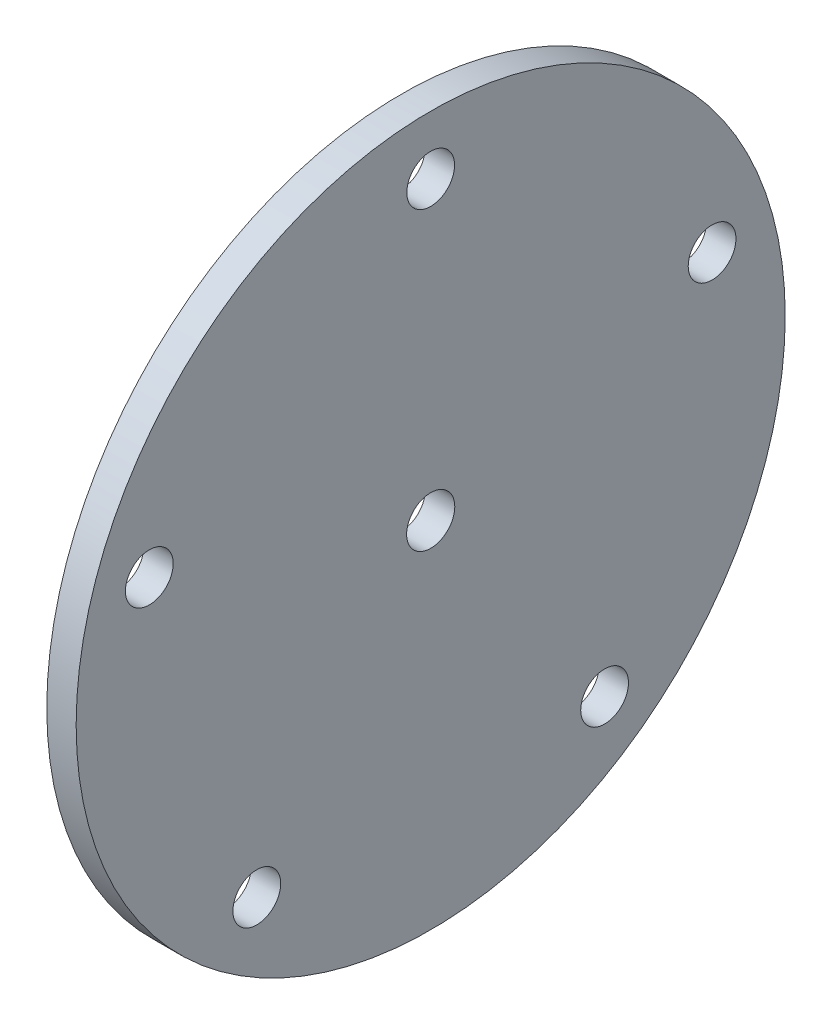
SolidWorks part; units mm, degrees
material "6061 Alloy"
ref_plane "Front Plane" through (0, 0, 0) normal (0, 0, 1) x (1, 0, 0)
ref_plane "Top Plane" through (0, 0, 0) normal (0, 1, 0) x (1, 0, 0)
ref_plane "Right Plane" through (0, 0, 0) normal (1, 0, 0) x (0, 0, -1)
sketch "Sketch1" plane through (0, 0, 0) normal (1, 0, 0) x (0, 0, -1)
  circle A0 centre (0, 0) radius 60.325
  dimension "D1" = 120.65
extrude "Boss-Extrude1" add sketch "Sketch1" along normal mid plane 5
sketch "Sketch2" plane through (-2.5, 0, 0) normal (-1, 0, 0) x (0, 0, 1)
  line L0 (0, 60.325) -> (0, -60.325) construction
  circle A1 centre (0, 0) radius 60.325 construction
  circle A10 centre (0, 50.343) radius 4.064
  circle A11 centre (47.879, 15.5568) radius 4.064
  circle A12 centre (29.5908, -40.7283) radius 4.064
  circle A13 centre (-29.5908, -40.7283) radius 4.064
  circle A14 centre (-47.879, 15.5568) radius 4.064
extrude "Cut-Extrude1" cut sketch "Sketch2" against normal through all
sketch "Sketch8" plane through (2.5, 0, 0) normal (1, 0, 0) x (0, 0, -1)
  line L0 (0, -8.5) -> (0, 12) construction
  circle A1 centre (0, 0) radius 4.1
  dimension "D1" = 8.2
extrude "Cut-Extrude4" cut sketch "Sketch8" against normal through all
